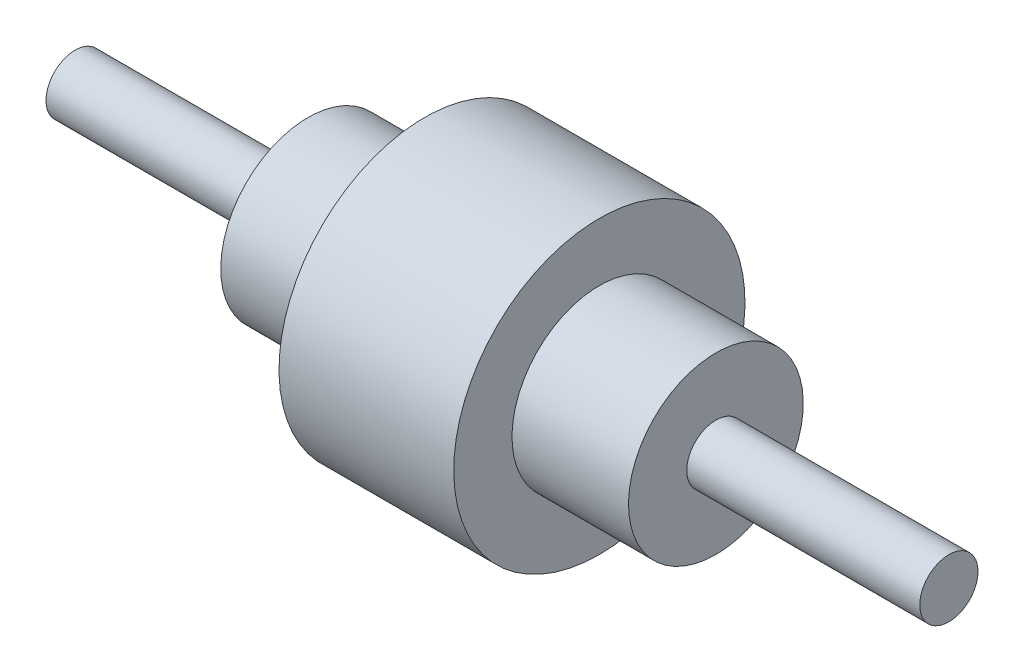
SolidWorks part; units mm, degrees
ref_plane "Front Plane" through (0, 0, 0) normal (0, 0, 1) x (1, 0, 0)
ref_plane "Top Plane" through (0, 0, 0) normal (0, 1, 0) x (1, 0, 0)
ref_plane "Right Plane" through (0, 0, 0) normal (1, 0, 0) x (0, 0, -1)
sketch "Sketch1" plane through (0, 0, 0) normal (0, 0, 1) x (1, 0, 0)
  line L0 (-30, 50) -> (30, 50)
  line L4 (30, 30) -> (70, 30)
  line L5 (-70, 30) -> (-70, 10)
  line L6 (-150, 0) -> (150, 0)
  line L7 (70, 10) -> (150, 10)
  line L8 (150, 10) -> (150, 0)
  line L9 (-30, 50) -> (-30, 30)
  line L10 (-30, 30) -> (-70, 30)
  line L11 (70, 30) -> (70, 10)
  line L12 (30, 50) -> (30, 30)
  line L13 (-70, 10) -> (-150, 10)
  line L14 (-150, 10) -> (-150, 0)
  point P3 (0, 50)
  dimension "D2" = 60
  dimension "D3" = 10
revolve "Revolve5" add sketch "Sketch1" angle 360 about L6
